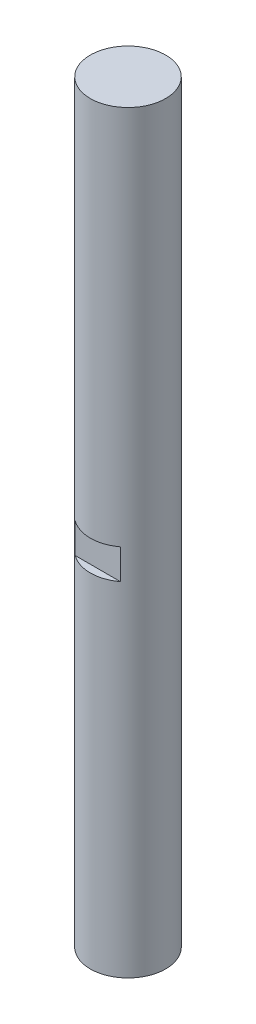
SolidWorks part; units mm, degrees
material "Хромистая нержавеющая сталь"
ref_plane "Спереди" through (0, 0, 0) normal (0, 0, 1) x (1, 0, 0)
ref_plane "Сверху" through (0, 0, 0) normal (0, 1, 0) x (1, 0, 0)
ref_plane "Справа" through (0, 0, 0) normal (1, 0, 0) x (0, 0, -1)
sketch "Эскиз1" plane through (0, 0, 0) normal (0, 1, 0) x (1, 0, 0)
  circle A0 centre (0, 0) radius 5
  dimension "D1" = 10
extrude "Бобышка-Вытянуть1" add sketch "Эскиз1" along normal blind 100
sketch "Эскиз2" plane through (0, 0, 0) normal (0, -1, 0) x (1, 0, 0)
  line L0 (-3, 4) -> (3, 4)
  circle A1 centre (0, 0) radius 5
  arc A2 (3, 4) -> (-3, 4) centre (0, 0) ccw
  dimension "D2" = 4
  dimension "D1" = 0
extrude "Вырез-Вытянуть1" cut sketch "Эскиз2" against normal blind 4 from offset 45.5
